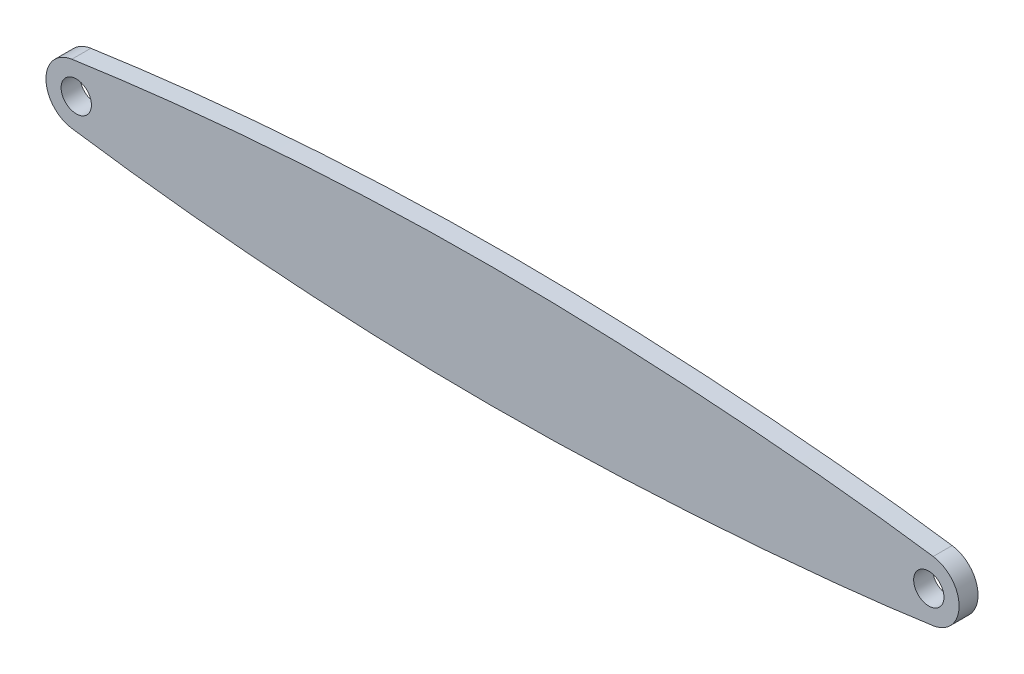
SolidWorks part; units mm, degrees
ref_plane "前视基准面" through (0, 0, 0) normal (0, 0, 1) x (1, 0, 0)
ref_plane "上视基准面" through (0, 0, 0) normal (0, 1, 0) x (1, 0, 0)
ref_plane "右视基准面" through (0, 0, 0) normal (1, 0, 0) x (0, 0, -1)
other "Configuration Table"
sketch "草图1" plane through (0, 0, 0) normal (0, 0, 1) x (1, 0, 0)
  line L0 (0, 0) -> (450, 0) construction
  line L1 (225, 0) -> (225, 55.0745) construction
  circle A0 centre (0, 0) radius 8
  arc A1 (-2.3136, 15.8318) -> (-2.3136, -15.8318) centre (0, 0) ccw
  circle A2 centre (450, 0) radius 8
  arc A3 (452.3136, -15.8318) -> (452.3136, 15.8318) centre (450, 0) ccw
  spline S0 degree 3 poles (-2.3136, 15.8318) (61.8427, 25.2073) (219.5721, 39.191) (399.0131, 23.6209) (452.3136, 15.8318) knots 0 0 0 0 0.5 1 1 1 1
  spline S1 degree 3 poles (-2.3136, -15.8318) (61.8427, -25.2073) (219.5721, -39.191) (399.0131, -23.6209) (452.3136, -15.8318) knots 0 0 0 0 0.5 1 1 1 1
  dimension "D1" = 450
extrude "凸台-拉伸1" add sketch "草图1" along normal blind 10
